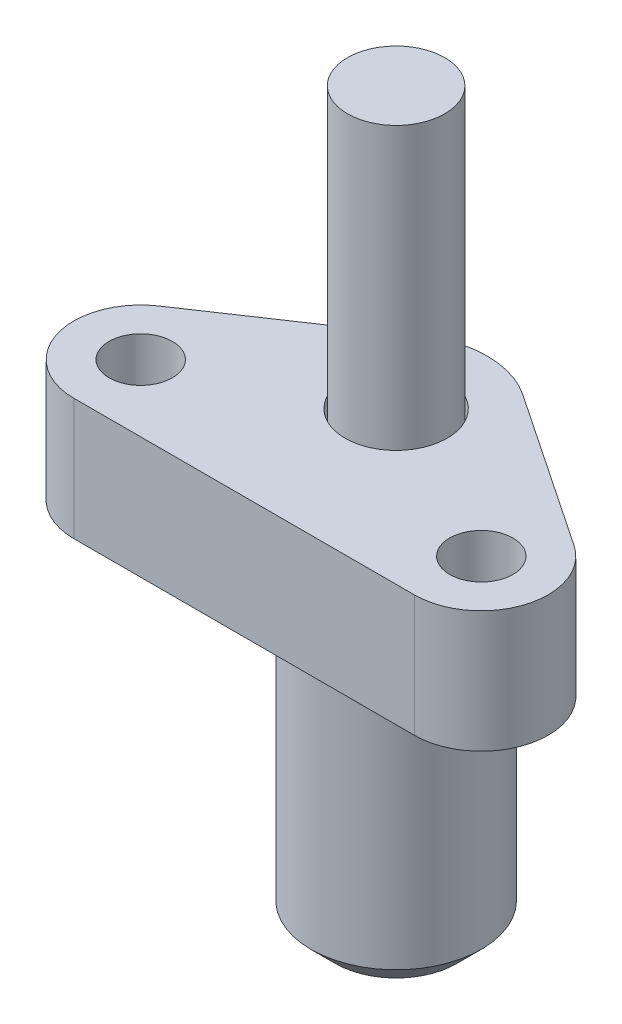
SolidWorks part; units mm, degrees
ref_plane "前视基准面" through (0, 0, 0) normal (0, 0, 1) x (1, 0, 0)
ref_plane "上视基准面" through (0, 0, 0) normal (0, 1, 0) x (1, 0, 0)
ref_plane "右视基准面" through (0, 0, 0) normal (1, 0, 0) x (0, 0, -1)
sketch "草图1" plane through (0, 0, 0) normal (0, 1, 0) x (1, 0, 0)
  circle A0 centre (0, 0) radius 2
  dimension "D1" = 4
extrude "凸台-拉伸1" add sketch "草图1" along normal blind 30
ref_plane "基准面1" through (0, 13.5, 0) normal (0, -1, 0) x (-1, 0, 0)
sketch "草图2" plane through (0, 13.5, 0) normal (0, -1, 0) x (-1, 0, 0)
  line L0 (0, 6.9784) -> (0, -3.5) construction
  line L1 (-7, -3.5) -> (7, -3.5) construction
  line L2 (-8.534, -1.2176) -> (-2.0919, 3.1123)
  line L3 (2.0919, 3.1123) -> (8.534, -1.2176)
  line L4 (-7, -6.25) -> (7, -6.25)
  circle A0 centre (-7, -3.5) radius 1.3
  circle A1 centre (7, -3.5) radius 1.3
  arc A2 (-1.3463, -3.5) -> (1.3463, -3.5) centre (0, 0) ccw construction
  arc A3 (-8.534, -1.2176) -> (-7, -6.25) centre (-7, -3.5) ccw
  arc A4 (8.534, -1.2176) -> (7, -6.25) centre (7, -3.5) cw
  arc A5 (2.0919, 3.1123) -> (-2.0919, 3.1123) centre (0, 0) ccw
  circle A6 centre (0, 0) radius 2.1
  point P5 (0, -3.5)
  dimension "D2" = 2.6
  dimension "D3" = 3.5
  dimension "D4" = 7.5
  dimension "D5" = 5.5
  dimension "D6" = 4.2
  dimension "D1" = 14
extrude "凸台-拉伸2" add sketch "草图2" against normal blind 5
sketch "草图3" plane through (0, 13.5, 0) normal (0, -1, 0) x (1, 0, 0)
  circle A0 centre (0, 0) radius 3.5
  circle A4 centre (0, 0) radius 2.1
  circle A5 centre (0, 0) radius 2 construction
  dimension "D1" = 4.2
  dimension "D2" = 7
extrude "凸台-拉伸4" add sketch "草图3" along normal up to surface (13.5 mm away) up to face at (0, 0, 2)
chamfer "倒角2" distance 1 angle 45 1 edges at (0, 0, 3.5)
fillet "圆角2" radius 0.5 1 edges at (0, 13.5, -3.5)
